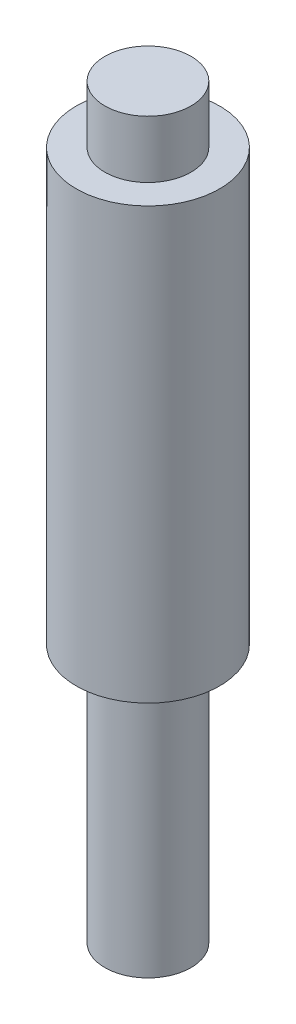
SolidWorks part; units mm, degrees
ref_plane "Front Plane" through (0, 0, 0) normal (0, 0, 1) x (1, 0, 0)
ref_plane "Top Plane" through (0, 0, 0) normal (0, 1, 0) x (1, 0, 0)
ref_plane "Right Plane" through (0, 0, 0) normal (1, 0, 0) x (0, 0, -1)
sketch "Sketch1" plane through (0, 0, 0) normal (0, 0, 1) x (1, 0, 0)
  line L0 (0, -11.6601) -> (0, -37.6601)
  line L1 (0, -37.6601) -> (-1.5, -37.6601)
  line L2 (-1.5, -37.6601) -> (-1.5, -28.6601)
  line L3 (-1.5, -28.6601) -> (-2.5, -28.6601)
  line L4 (-2.5, -28.6601) -> (-2.5, -13.6601)
  line L5 (-2.5, -13.6601) -> (-1.5, -13.6601)
  line L6 (-1.5, -13.6601) -> (-1.5, -11.6601)
  line L7 (-1.5, -11.6601) -> (0, -11.6601)
  dimension "D1" = 2
  dimension "D2" = 2.5
  dimension "D3" = 1.5
  dimension "D4" = 1.5
  dimension "D5" = 15
  dimension "D6" = 9
revolve "Revolve1" add sketch "Sketch1" angle 360 about L0
